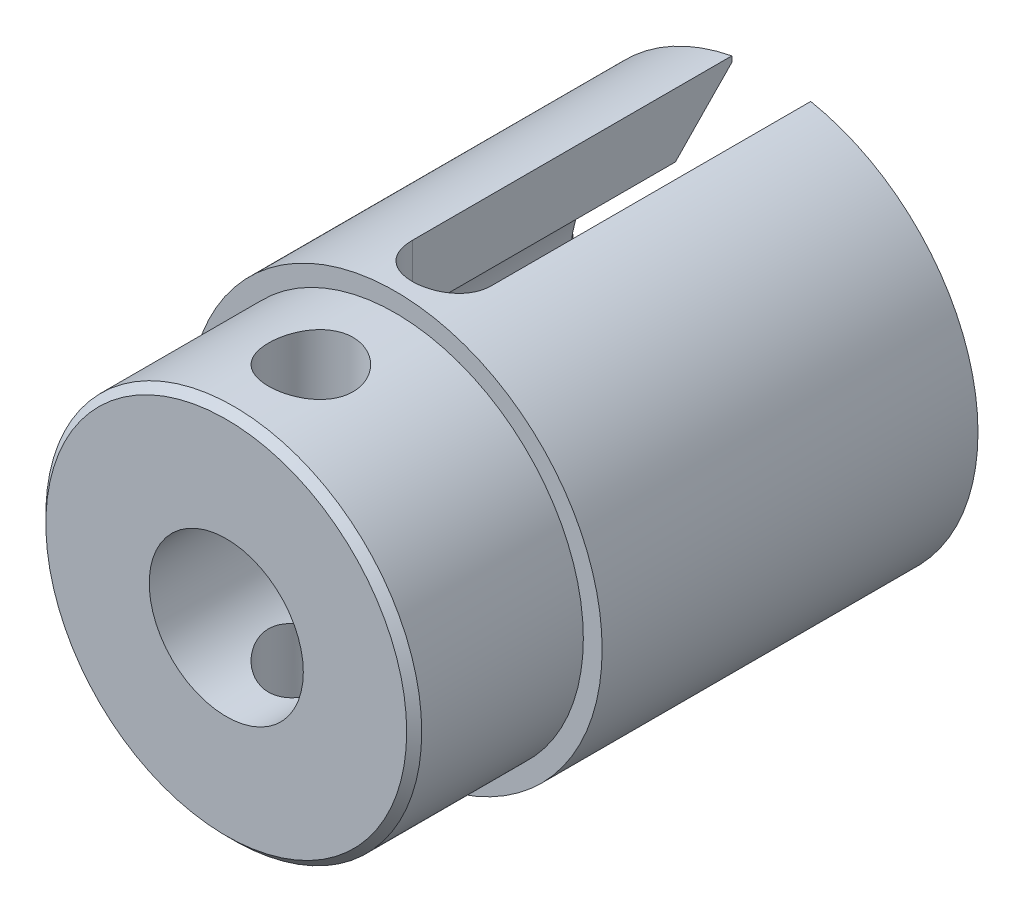
SolidWorks part; units mm, degrees
material "7075-O (SS)"
ref_plane "前视基准面" through (0, 0, 0) normal (0, 0, 1) x (1, 0, 0)
ref_plane "上视基准面" through (0, 0, 0) normal (0, 1, 0) x (1, 0, 0)
ref_plane "右视基准面" through (0, 0, 0) normal (1, 0, 0) x (0, 0, -1)
sketch "草图1" plane through (0, 0, 0) normal (0, 0, 1) x (1, 0, 0)
  circle A0 centre (0, 0) radius 11
  dimension "D1" = 22
extrude "凸台-拉伸1" add sketch "草图1" along normal blind 29
sketch "草图2" plane through (0, 0, 29) normal (0, 0, 1) x (1, 0, 0)
  circle A0 centre (0, 0) radius 10
  dimension "D1" = 20
extrude "切除-拉伸1" cut sketch "草图2" against normal blind 9 flip side to cut
sketch "草图3" plane through (0, 0, 0) normal (0, 0, -1) x (-1, 0, 0)
  circle A0 centre (0, 0) radius 7.7
  dimension "D1" = 15.4
extrude "切除-拉伸2" cut sketch "草图3" against normal blind 20
sketch "草图4" plane through (0, 0, 0) normal (0, 1, 0) x (1, 0, 0)
  line L0 (-2.1, -17) -> (-2.1, 0)
  line L1 (11, 0) -> (-11, 0) construction
  line L2 (2.1, -17) -> (2.1, 0)
  line L3 (7.7, 0) -> (-7.7, 0) construction
  line L4 (2.1, 0) -> (-2.1, 0)
  circle A0 centre (0, -17) radius 2.1
  dimension "D2" = 4.2
  dimension "D1" = 17
extrude "切除-拉伸3" cut sketch "草图4" against normal mid plane 50 contours A0 L2 L4 L0 | A0
chamfer "倒角1" distance 3 angle 45 2 edges at (7.7, 0, 0) (-7.7, 0, 0)
sketch "草图5" plane through (0, 0, 29) normal (0, 0, 1) x (1, 0, 0)
  circle A1 centre (0, 0) radius 10
  circle A2 centre (0, 0) radius 10
  dimension "D1" = 0
extrude "凸台-拉伸2" add sketch "草图5" along normal blind 10
sketch "草图6" plane through (0, 0, 39) normal (0, 0, 1) x (1, 0, 0)
  line L0 (-3.1225, 2.5) -> (3.1225, 2.5)
  circle A0 centre (0, 0) radius 4
  dimension "D1" = 8
  dimension "D2" = 2.5
extrude "切除-拉伸5" cut sketch "草图6" against normal up to surface (19 mm away) contours L0 A0
sketch "草图7" plane through (0, 0, 39) normal (0, 0, 1) x (1, 0, 0)
  line L3 (3.1702, 2.6) -> (-3.1702, 2.6)
  line L4 (3.1702, 2.6) -> (-3.1702, 2.6)
  arc A2 (-3.1702, 2.6) -> (3.1702, 2.6) centre (0, 0) ccw
  arc A3 (-3.1702, 2.6) -> (3.1702, 2.6) centre (0, 0) ccw
  dimension "D1" = 0.1
extrude "切除-拉伸6" cut sketch "草图7" against normal up to surface (19 mm away) up to face at (-7.7, 0, 20)
sketch "草图8" plane through (0, 0, 39) normal (0, 0, 1) x (1, 0, 0)
  circle A0 centre (0, 0) radius 7.5
  dimension "D1" = 15
chamfer "倒角2" distance 0.4 angle 45 2 edges at (0, 2.6, 39) (0, -4.1, 39)
sketch "草图12" plane through (0, 0, 39) normal (0, 0, 1) x (1, 0, 0)
  circle A1 centre (0, 0) radius 10
  circle A2 centre (0, 0) radius 10
  dimension "D1" = 0
extrude "切除-拉伸9" cut sketch "草图12" against normal offset from surface (10 mm away) 9 up to face at (10, 0, 20)
sketch "草图13" plane through (0, 0, 29) normal (0, 0, 1) x (1, 0, 0)
  circle A0 centre (0, 0) radius 4.1
  dimension "D1" = 8.2
extrude "切除-拉伸10" cut sketch "草图13" against normal up to surface (9 mm away) up to face at (0, -0.75, 20)
sketch "草图14" plane through (0, 0, 0) normal (0, 1, 0) x (1, 0, 0)
  line L0 (-10, -29) -> (10, -29) construction
  circle A0 centre (0, -24.5) radius 2.25
  dimension "D1" = 4.5
  dimension "D2" = 4.5
extrude "切除-拉伸11" cut sketch "草图14" against normal mid plane 50
chamfer "倒角3" distance 0.4 angle 45 1 edges at (10, 0, 29)
